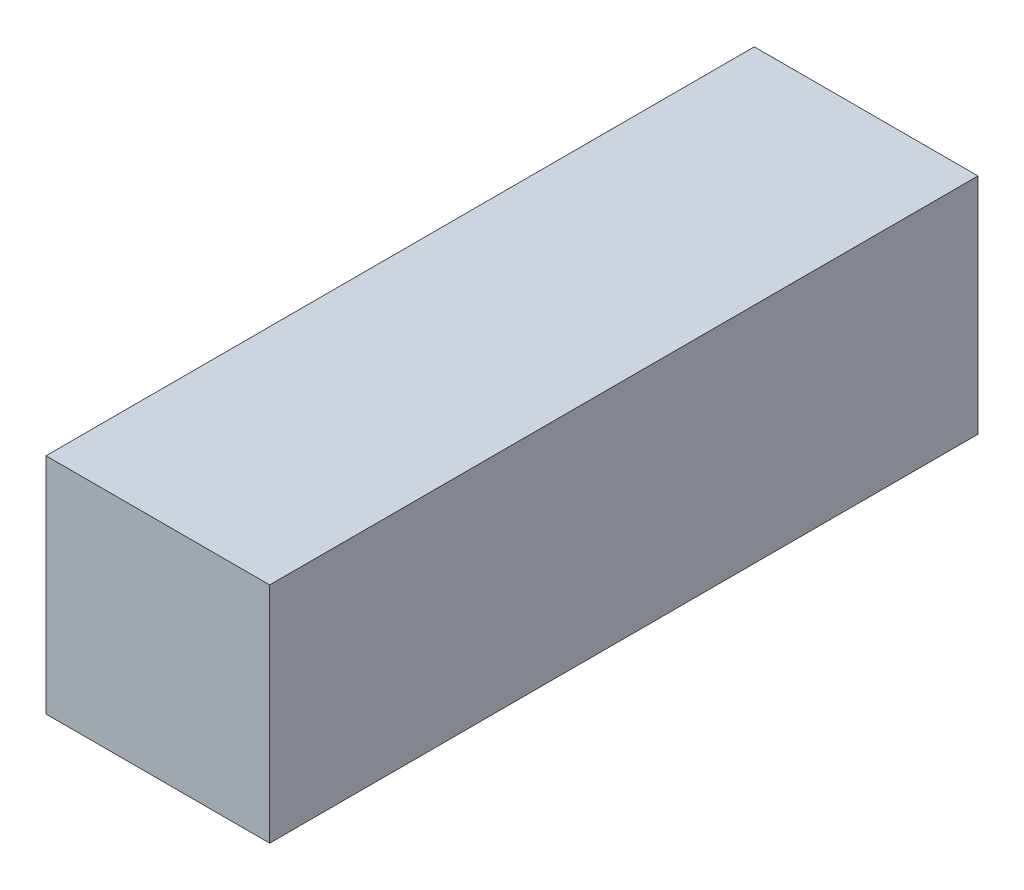
SolidWorks part; units mm, degrees
material "Cast Alloy Steel"
ref_plane "Front Plane" through (0, 0, 0) normal (0, 0, 1) x (1, 0, 0)
ref_plane "Top Plane" through (0, 0, 0) normal (0, 1, 0) x (1, 0, 0)
ref_plane "Right Plane" through (0, 0, 0) normal (1, 0, 0) x (0, 0, -1)
sketch "Sketch1" plane through (0, 0, 0) normal (0, 0, 1) x (1, 0, 0)
  line L1 (-1.5, 1.5) -> (1.5, 1.5)
  line L2 (-1.5, 1.5) -> (-1.5, -1.5)
  line L3 (-1.5, -1.5) -> (1.5, -1.5)
  line L4 (1.5, 1.5) -> (1.5, -1.5)
  line L5 (-1.5, 1.5) -> (1.5, -1.5) construction
  line L6 (-1.5, -1.5) -> (1.5, 1.5) construction
  point P0 (0, 0)
  dimension "D1" = 3
extrude "Boss-Extrude1" add sketch "Sketch1" along normal blind 9.5
move or copy body "Body-Move/Copy1" [suppressed] bodies to move or copy 101
